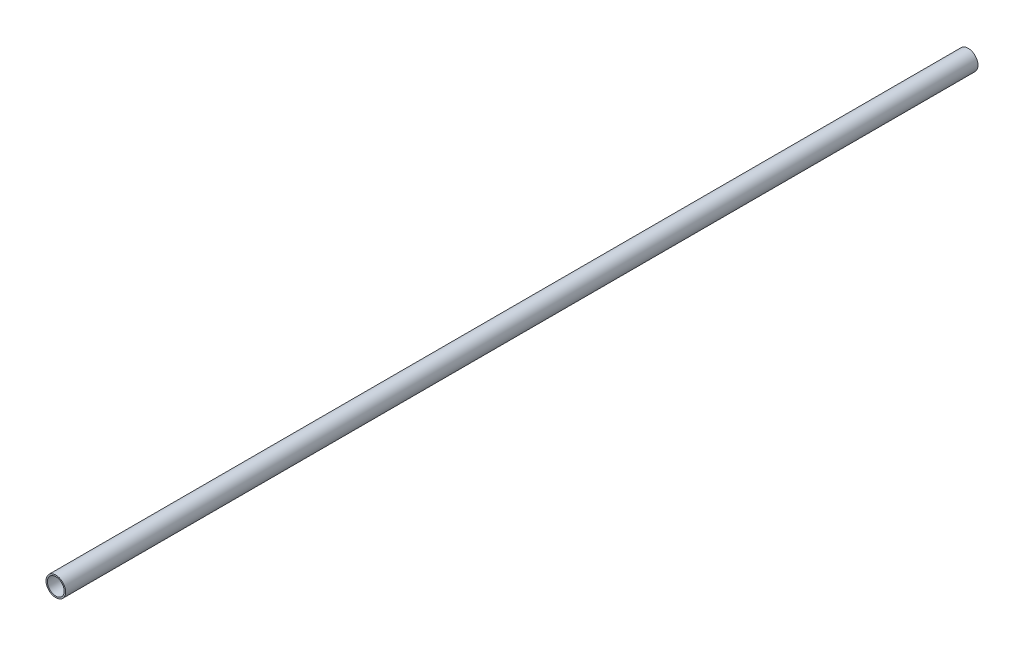
SolidWorks part; units mm, degrees
material "Poltrusion Carbon Fiber"
ref_plane "Front Plane" through (0, 0, 0) normal (0, 0, 1) x (1, 0, 0)
ref_plane "Top Plane" through (0, 0, 0) normal (0, 1, 0) x (1, 0, 0)
ref_plane "Right Plane" through (0, 0, 0) normal (1, 0, 0) x (0, 0, -1)
sketch "Эскиз1" plane through (0, 0, 0) normal (0, 0, 1) x (1, 0, 0)
  circle A0 centre (0, 0) radius 7
  circle A1 centre (0, 0) radius 6
  dimension "D1" = 14
  dimension "D2" = 1
extrude "Бобышка-Вытянуть1" add sketch "Эскиз1" along normal mid plane 650
